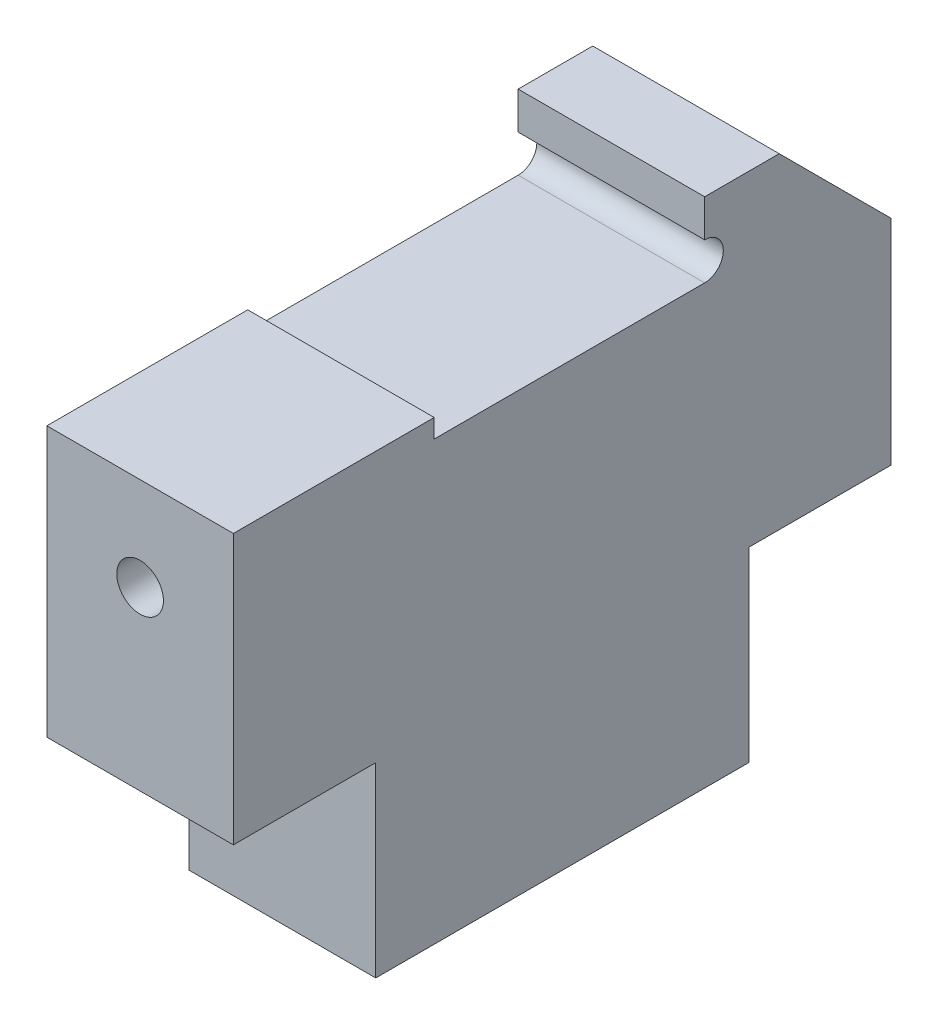
SolidWorks part; units mm, degrees
ref_plane "Front Plane" through (0, 0, 0) normal (0, 0, 1) x (1, 0, 0)
ref_plane "Top Plane" through (0, 0, 0) normal (0, 1, 0) x (1, 0, 0)
ref_plane "Right Plane" through (0, 0, 0) normal (1, 0, 0) x (0, 0, -1)
sketch "Sketch1" plane through (0, 0, 0) normal (1, 0, 0) x (0, 0, -1)
  line L0 (0, 1) -> (0, 3)
  line L1 (0, -1) -> (-14.5, -1)
  line L2 (-14.5, -1) -> (-14.5, 0)
  line L3 (-14.5, 0) -> (-25.27, 0)
  line L4 (-25.27, 0) -> (-25.27, -14.46)
  line L5 (-25.27, -14.46) -> (-17.635, -14.46)
  line L6 (-17.635, -14.46) -> (-17.635, -24.46)
  line L7 (-17.635, -24.46) -> (2.365, -24.46)
  line L8 (2.365, -24.46) -> (2.365, -14.46)
  line L9 (2.365, -14.46) -> (10, -14.46)
  line L10 (10, -14.46) -> (10, 3)
  line L11 (10, 3) -> (0, 3)
  arc A0 (0, -1) -> (0, 1) centre (0, 0) ccw
  dimension "D2" = 2
  dimension "D1" = 14.46
  dimension "D3" = 2
  dimension "D4" = 10
  dimension "D5" = 14.5
  dimension "D6" = 25.27
  dimension "D7" = 20
  dimension "D9" = 10
extrude "Boss-Extrude1" add sketch "Sketch1" against normal blind 10
chamfer "Chamfer1" distance 6 angle 45 1 edges at (-5, 3, -10)
sketch "Sketch2" plane through (0, 0, 25.27) normal (0, 0, 1) x (1, 0, 0)
  line L0 (-5, 0) -> (-5, -5) construction
  line L1 (-10, 0) -> (0, 0) construction
  dimension "D1" = 5
hole_wizard "M3x0.5 Tapped Hole1" positions "3DSketch1" profile "Sketch4" tap size "M3x0.5" standard "ANSI Metric"
sketch3d "3DSketch1"
  point P0 (-5, -5, 25.27)
sketch "Sketch4" plane through (-5, -5, 25.27) normal (1, 0, 0) x (0, -1, 0)
  line L0 (0, 0) -> (0, 15.2511)
  line L1 (0, 15.2511) -> (1.25, 14.5)
  line L2 (1.25, 14.5) -> (1.25, 0)
  line L5 (1.25, 0) -> (0, 0)
  line L10 (0, 15.2511) -> (-1.25, 14.5) construction
  line L11 (0, -6.35) -> (0, 107.95) construction
  dimension "Tap Drill Dia." = 2.5
  dimension "Tap Drill Depth" = 14.5
  dimension "Drill Angle" = 118
cosmetic thread "Hole Thread1" parameters "D1"=12, "D2"=3
